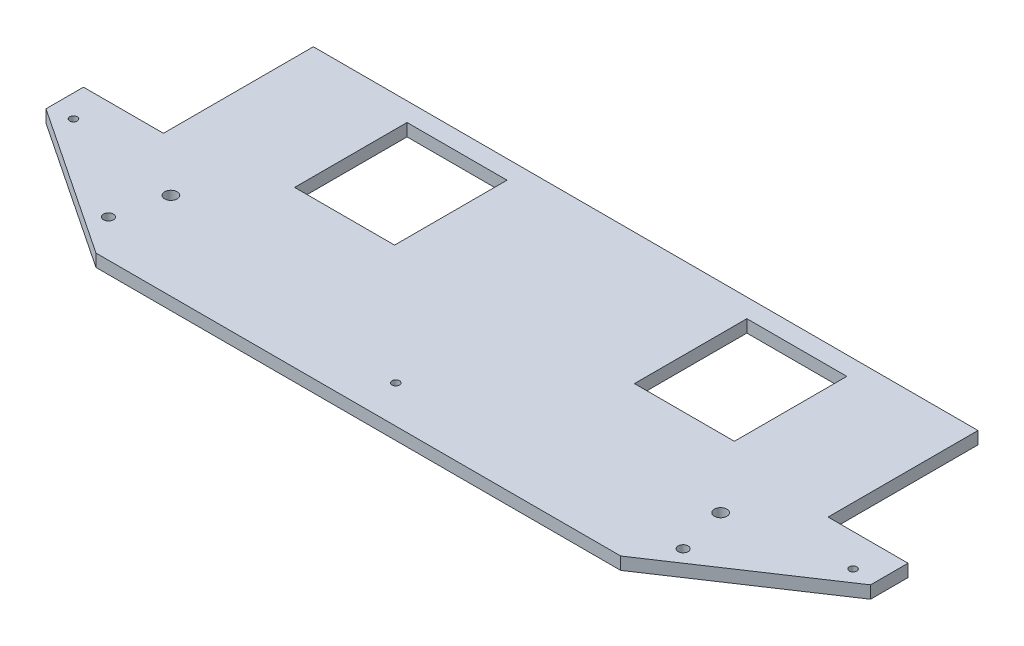
SolidWorks part; units mm, degrees
material "3.3535 (EN-AW 5754)"
ref_plane "Plan de face" through (0, 0, 0) normal (0, 0, 1) x (1, 0, 0)
ref_plane "Plan de dessus" through (0, 0, 0) normal (0, 1, 0) x (1, 0, 0)
ref_plane "Plan de droite" through (0, 0, 0) normal (1, 0, 0) x (0, 0, -1)
sketch "Esquisse1" plane through (0, 0, 0) normal (0, 1, 0) x (1, 0, 0)
  line L1 (-54.824, 233.7469) -> (275.176, 233.7469)
  line L2 (-54.824, 233.7469) -> (-54.824, -16.2531)
  line L3 (-54.824, -16.2531) -> (275.176, -16.2531)
  line L4 (275.176, 233.7469) -> (275.176, -16.2531)
  dimension "D1" = 330
  dimension "D2" = 250
extrude "Extrusion1" add sketch "Esquisse1" along normal blind 5
sketch "Esquisse2" plane through (0, 5, 0) normal (0, 1, 0) x (-1, 0, 0)
  line L2 (54.824, -233.7469) -> (54.824, 16.2531) construction
  line L3 (54.824, -218.7469) -> (22.824, -218.7469)
  line L4 (54.824, -218.7469) -> (54.824, -158.7469)
  line L5 (54.824, -158.7469) -> (22.824, -158.7469)
  line L6 (22.824, -218.7469) -> (22.824, -158.7469)
  line L7 (-275.176, -233.7469) -> (54.824, -233.7469) construction
  line L8 (-110.176, -233.7469) -> (-110.176, 16.2531) construction
  line L9 (54.824, 16.2531) -> (-275.176, 16.2531) construction
  line L10 (-243.176, -218.7469) -> (-243.176, -158.7469)
  line L11 (-275.176, -158.7469) -> (-243.176, -158.7469)
  line L12 (-275.176, -218.7469) -> (-275.176, -158.7469)
  line L13 (-275.176, -218.7469) -> (-243.176, -218.7469)
  dimension "D1" = 15
  dimension "D2" = 60
  dimension "D3" = 32
extrude "Enlèv. mat.-Extru.1" cut sketch "Esquisse2" against normal through all
sketch "Esquisse4" plane through (0, 5, 0) normal (0, 1, 0) x (-1, 0, 0)
  line L1 (-198.176, -211.2469) -> (-158.176, -211.2469)
  line L2 (-198.176, -211.2469) -> (-198.176, -166.2469)
  line L3 (-198.176, -166.2469) -> (-158.176, -166.2469)
  line L4 (-158.176, -211.2469) -> (-158.176, -166.2469)
  line L6 (-243.176, -158.7469) -> (-275.176, -158.7469) construction
  line L8 (-22.176, -211.2469) -> (-62.176, -211.2469)
  line L9 (-22.176, -211.2469) -> (-22.176, -166.2469)
  line L10 (-22.176, -166.2469) -> (-62.176, -166.2469)
  line L11 (-62.176, -211.2469) -> (-62.176, -166.2469)
  line L12 (54.824, -158.7469) -> (22.824, -158.7469) construction
  line L13 (-243.176, -218.7469) -> (-243.176, -158.7469) construction
  line L14 (22.824, -158.7469) -> (22.824, -218.7469) construction
  dimension "D1" = 40
  dimension "D2" = 45
  dimension "D3" = 45
  dimension "D4" = 7.5
  dimension "D5" = 40
  dimension "D6" = 45
  dimension "D7" = 45
  dimension "D8" = 7.5
extrude "Enlèv. mat.-Extru.2" cut sketch "Esquisse4" against normal through all
chamfer "Chanfrein1" distance 15 angle 45 2 edges at (-54.824, 2.5, 16.2531) (275.176, 2.5, 16.2531)
sketch "Esquisse5" plane through (0, 0, -233.7469) normal (0, 0, -1) x (-1, 0, 0)
  line L1 (-275.176, 5) -> (54.824, 5)
  line L2 (-275.176, 5) -> (-275.176, 0)
  line L3 (-275.176, 0) -> (54.824, 0)
  line L4 (54.824, 5) -> (54.824, 0)
extrude "Enlèv. mat.-Extru.3" cut sketch "Esquisse5" against normal blind 15
sketch "Esquisse8" plane through (0, 5, 0) normal (0, 1, 0) x (-1, 0, 0)
  line L0 (39.824, 16.2531) -> (-260.176, 16.2531) construction
  line L1 (54.824, -158.7469) -> (54.824, 1.2531) construction
  line L2 (-7.9279, -83.7469) -> (-15.2136, -83.7469) construction
  line L3 (-129.176, -33.7469) -> (-129.176, -25.109) construction
  line L4 (-95.176, -83.7469) -> (-95.176, 16.2531) construction
  line L5 (-129.176, -33.7469) -> (-195.176, 16.2531)
  line L6 (-195.176, 16.2531) -> (-25.176, 16.2531)
  line L7 (-25.176, 16.2531) -> (-61.176, -33.7469)
  line L9 (-275.176, 1.2531) -> (-275.176, -158.7469) construction
  spline S0 degree 3 poles (-95.176, -83.7469) (-117.7963, -83.7469) (-129.176, -53.9018) (-129.176, -33.7469) knots 0 0 0 0 1 1 1 1
  spline S1 degree 3 poles (-95.176, -83.7469) (-72.5556, -83.7469) (-61.176, -53.9018) (-61.176, -33.7469) knots 0 0 0 0 1 1 1 1
  point P2 (-95.176, -83.7469)
  point P3 (-129.176, -33.7469)
  dimension "D1" = 50
  dimension "D2" = 100
  dimension "D3" = 150
  dimension "D4" = 34
  dimension "D5" = 80
  dimension "D6" = 80
extrude "Enlèv. mat.-Extru.5" cut sketch "Esquisse8" against normal through all
sketch "Esquisse9" plane through (0, 5, 0) normal (0, 1, 0) x (-1, 0, 0)
  line L0 (-275.176, 1.2531) -> (-275.176, -158.7469) construction
  line L1 (54.824, -158.7469) -> (54.824, 1.2531) construction
  line L2 (39.824, 16.2531) -> (-25.176, 16.2531) construction
  line L3 (-195.176, 16.2531) -> (-260.176, 16.2531) construction
  circle A0 centre (-205.176, -33.7469) radius 17.5
  circle A1 centre (-15.176, -33.7469) radius 17.5
  dimension "D1" = 35
  dimension "D2" = 35
  dimension "D3" = 70
  dimension "D4" = 70
  dimension "D5" = 50
  dimension "D6" = 50
extrude "Enlèv. mat.-Extru.6" cut sketch "Esquisse9" against normal through all
sketch "Sketch1" plane through (0, 0, 0) normal (0, -1, 0) x (1, 0, 0)
  line L0 (62.176, -188.7469) -> (158.176, -188.7469) construction
  line L1 (62.176, -166.2469) -> (62.176, -211.2469) construction
  line L2 (158.176, -211.2469) -> (158.176, -166.2469) construction
  line L3 (-54.824, -143.7469) -> (5.176, -103.7469)
  line L4 (95.176, -43.7469) -> (125.176, -43.7469) construction
  line L5 (215.176, -103.7469) -> (275.176, -143.7469)
  line L6 (275.176, -143.7469) -> (275.176, 16.2531)
  line L7 (275.176, 16.2531) -> (-54.824, 16.2531)
  line L8 (-54.824, 16.2531) -> (-54.824, -143.7469)
  line L9 (110.176, -188.7469) -> (110.176, -43.7469) construction
  line L10 (-39.824, 16.2531) -> (25.176, 16.2531) construction
  line L11 (5.176, -103.7469) -> (215.176, -103.7469)
  line L12 (110.176, -43.7469) -> (110.176, 16.2531) construction
  line L13 (-54.824, -158.7469) -> (-22.824, -158.7469) construction
  line L14 (-54.824, -158.7469) -> (-54.824, 1.2531) construction
  circle A0 centre (-4.824, -118.7469) radius 2
  circle A1 centre (225.176, -118.7469) radius 2
  point P18 (110.176, -103.7469)
  dimension "D12" = 50
  dimension "D14" = 4
  dimension "D15" = 6.9338
  dimension "D1" = 45
  dimension "D2" = 100
  dimension "D3" = 330
  dimension "D4" = 30
  dimension "D5" = 40
  dimension "D6" = 60
  dimension "D7" = 210
  dimension "D8" = 60
  dimension "D9" = 15
  dimension "D10" = 120
  dimension "D11" = 160
  dimension "D13" = 40
extrude "Extrude1" cut sketch "Sketch1" against normal blind 5
sketch "Esquisse10" plane through (0, 0, 0) normal (0, -1, 0) x (1, 0, 0)
  line L0 (110.176, -218.7469) -> (110.176, -103.7469) construction
  line L1 (243.176, -218.7469) -> (-22.824, -218.7469) construction
  line L2 (5.176, -103.7469) -> (215.176, -103.7469) construction
  line L3 (22.176, -211.2469) -> (22.176, -166.2469) construction
  line L5 (-54.824, -158.7469) -> (-22.824, -158.7469) construction
  line L6 (-54.824, -158.7469) -> (-54.824, -143.7469) construction
  circle A0 centre (0.176, -138.7469) radius 2.5
  circle A1 centre (220.176, -138.7469) radius 2.5
  circle A3 centre (-45.824, -145.7469) radius 1.5
  circle A4 centre (266.176, -145.7469) radius 1.5
  circle A5 centre (110.176, -118.7469) radius 1.5
  point P12 (22.176, -188.7469)
  dimension "D1" = 50
  dimension "D2" = 220
  dimension "D3" = 5
  dimension "D4" = 3
  dimension "D5" = 13
  dimension "D6" = 312
  dimension "D7" = 43
  dimension "D8" = 9
  dimension "D9" = 3
  dimension "D10" = 15
extrude "Enlèv. mat.-Extru.7" cut sketch "Esquisse10" against normal blind 6
